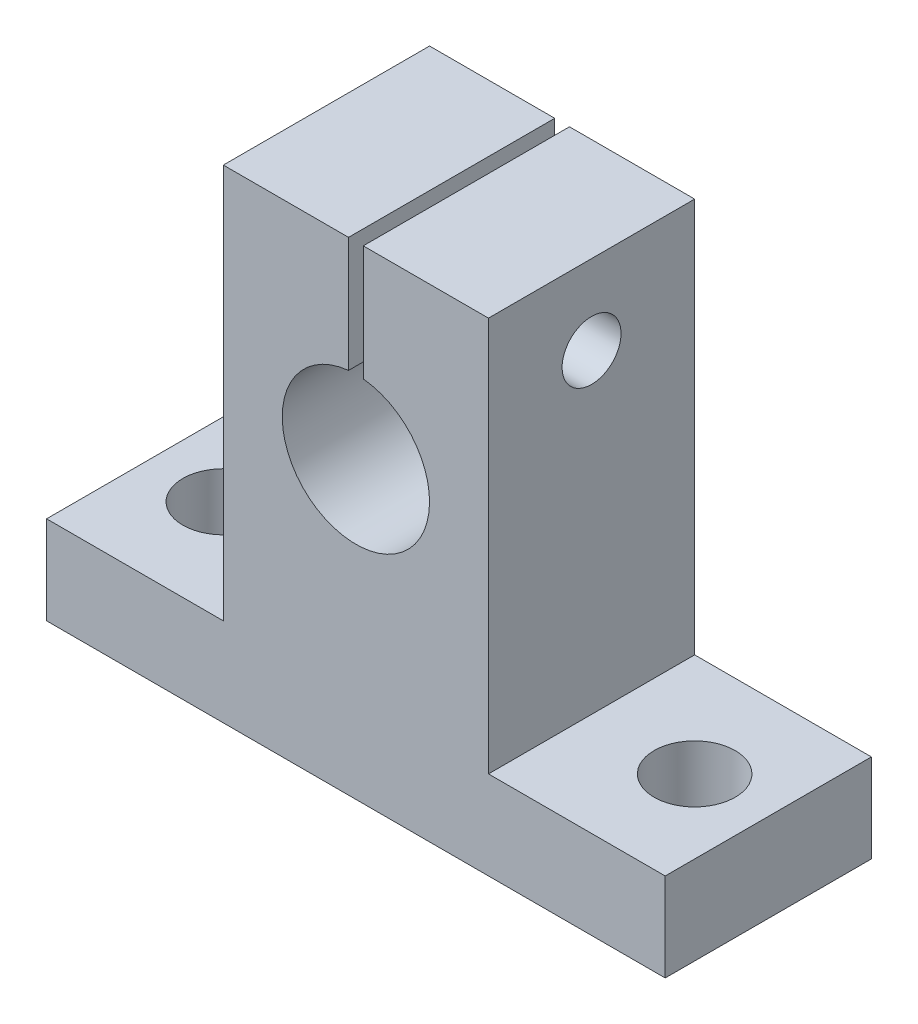
SolidWorks part; units mm, degrees
material "6061 合金"
ref_plane "前视基准面" through (0, 0, 0) normal (0, 0, 1) x (1, 0, 0)
ref_plane "上视基准面" through (0, 0, 0) normal (0, 1, 0) x (1, 0, 0)
ref_plane "右视基准面" through (0, 0, 0) normal (1, 0, 0) x (0, 0, -1)
sketch "草图3" plane through (0, 0, 0) normal (0, 0, 1) x (1, 0, 0)
  line L0 (-9, -13.4) -> (-21, -13.4)
  line L1 (-9, 13.4) -> (9, 13.4)
  line L2 (-9, 13.4) -> (-9, -13.4)
  line L3 (21, -13.4) -> (21, -19.4)
  line L4 (9, 13.4) -> (9, -13.4)
  line L5 (-9, 13.4) -> (9, -13.4) construction
  line L6 (-9, -13.4) -> (9, 13.4) construction
  line L7 (-21, -13.4) -> (-21, -19.4)
  line L8 (-21, -19.4) -> (21, -19.4)
  line L9 (0, 12.3832) -> (0, -26.3345) construction
  line L10 (9, -13.4) -> (21, -13.4)
  circle A0 centre (0, 0.6) radius 5
  point P0 (0, 0)
  point P14 (0, -19.4)
  dimension "D1" = 20
  dimension "D6" = 10
  dimension "D2" = 26.8
  dimension "D3" = 18
  dimension "D4" = 6
  dimension "D5" = 21
extrude "凸台-拉伸3" add sketch "草图3" along normal mid plane 14
sketch "草图5" plane through (0, -13.4, 0) normal (0, 1, 0) x (1, 0, 0)
  line L0 (0, 7.7672) -> (0, -15.7864) construction
  circle A0 centre (-16, 0) radius 2.75
  circle A1 centre (16, 0) radius 2.75
  dimension "D1" = 5.5
  dimension "D2" = 32
extrude "切除-拉伸1" cut sketch "草图5" against normal blind 10
sketch "草图6" plane through (0, 0, 7) normal (0, 0, 1) x (1, 0, 0)
  line L1 (-0.5, 16.5999) -> (0.5, 16.5999)
  line L2 (-0.5, 16.5999) -> (-0.5, 3.4601)
  line L3 (-0.5, 3.4601) -> (0.5, 3.4601)
  line L4 (0.5, 16.5999) -> (0.5, 3.4601)
  line L5 (-0.5, 16.5999) -> (0.5, 3.4601) construction
  line L6 (-0.5, 3.4601) -> (0.5, 16.5999) construction
  point P0 (0, 10.03)
  dimension "D1" = 1
extrude "切除-拉伸2" cut sketch "草图6" against normal up to surface (14 mm away) up to face at (0, -8.2, -7)
sketch "草图7" plane through (9, 0, 0) normal (1, 0, 0) x (0, 0, -1)
  circle A0 centre (0, 8) radius 2
  dimension "D1" = 4
  dimension "D2" = 8
extrude "切除-拉伸3" cut sketch "草图7" against normal through all
